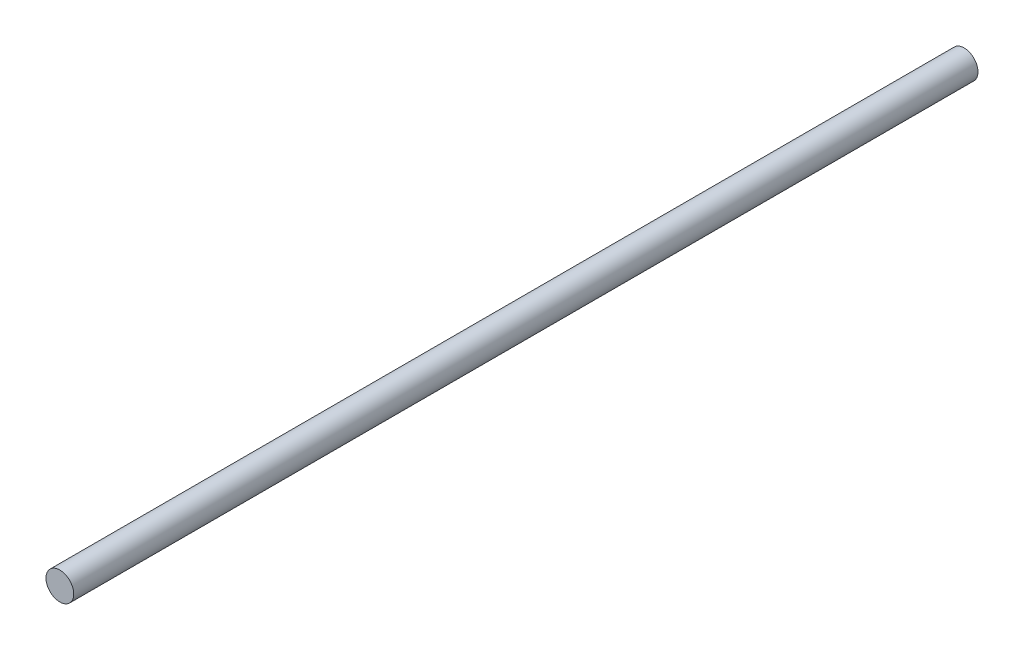
SolidWorks part; units mm, degrees
ref_plane "Alzado" through (0, 0, 0) normal (0, 0, 1) x (1, 0, 0)
ref_plane "Planta" through (0, 0, 0) normal (0, 1, 0) x (1, 0, 0)
ref_plane "Vista lateral" through (0, 0, 0) normal (1, 0, 0) x (0, 0, -1)
sketch "Croquis1" plane through (0, 0, 0) normal (0, 0, 1) x (1, 0, 0)
  circle A0 centre (0, 0) radius 9
  dimension "D1" = 18
extrude "Saliente-Extruir2" add sketch "Croquis1" against normal blind 587
